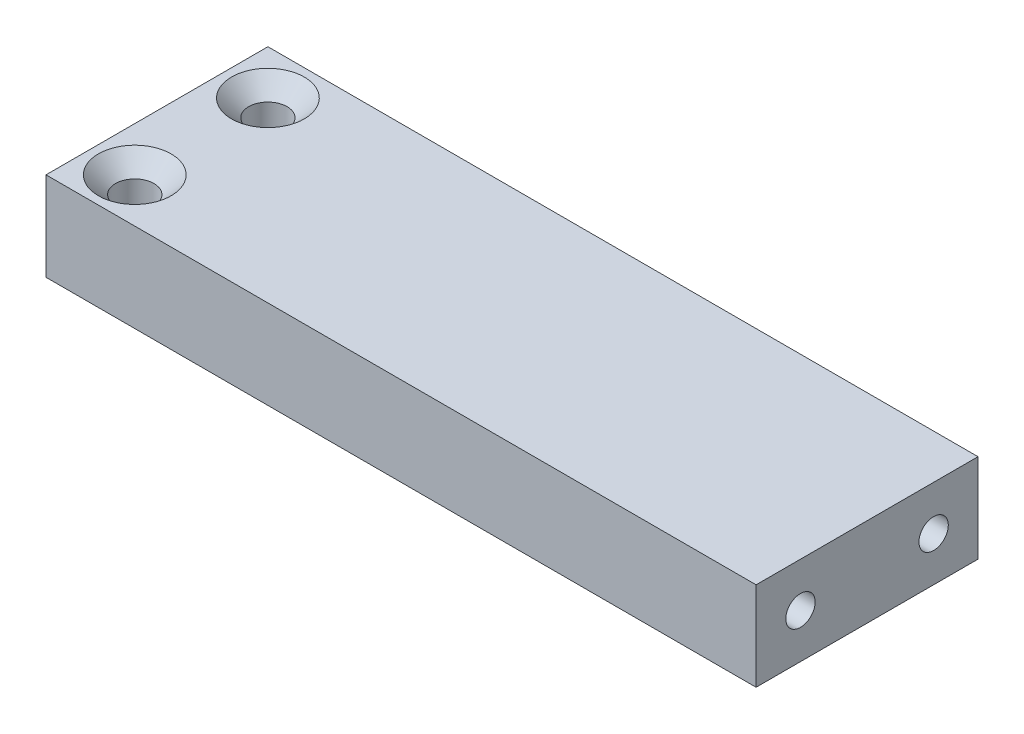
SolidWorks part; units mm, degrees
material "6061 Alloy"
ref_plane "Front" through (0, 0, 0) normal (0, 0, 1) x (1, 0, 0)
ref_plane "Top" through (0, 0, 0) normal (0, 1, 0) x (1, 0, 0)
ref_plane "Right" through (0, 0, 0) normal (1, 0, 0) x (0, 0, -1)
sketch "Sketch1" plane through (0, 0, 0) normal (0, 1, 0) x (1, 0, 0)
  line L1 (-50.8, -15.875) -> (50.8, -15.875)
  line L2 (-50.8, -15.875) -> (-50.8, 15.875)
  line L3 (-50.8, 15.875) -> (50.8, 15.875)
  line L4 (50.8, -15.875) -> (50.8, 15.875)
  line L5 (-50.8, -15.875) -> (50.8, 15.875) construction
  line L6 (-50.8, 15.875) -> (50.8, -15.875) construction
  point P0 (0, 0)
  dimension "D1" = 31.75
  dimension "D2" = 101.6
extrude "Boss-Extrude1" add sketch "Sketch1" along normal mid plane 12.7 contours L3 L4 L1 L2
sketch "Sketch2" plane through (50.8, 0, 0) normal (1, 0, 0) x (0, 0, -1)
  point P0 (-9.525, 0)
  point P1 (9.525, 0)
hole_wizard "M5x0.8 Tapped Hole1" positions "Sketch3" profile "Sketch5" tap size "M5x0.8" standard "ANSI Metric"
sketch "Sketch3" plane through (50.8, 0, 0) normal (1, 0, 0) x (0, 0, -1)
  point P0 (-9.525, 0)
  point P3 (9.525, 0)
sketch "Sketch5" plane through (50.8, 0, 9.525) normal (0, 1, 0) x (0, 0, -1)
  line L0 (0, 0) -> (0, 12.192)
  line L1 (0, 12.192) -> (2.1, 10.9302)
  line L2 (2.1, 10.9302) -> (2.1, 0)
  line L5 (2.1, 0) -> (0, 0)
  line L10 (0, 12.192) -> (-2.1, 10.9302) construction
  line L11 (0, -6.35) -> (0, 107.95) construction
  dimension "Tap Drill Dia." = 4.2
  dimension "Tap Drill Depth" = 12.192
  dimension "Drill Angle" = 118
cosmetic thread "Hole Thread2" parameters "D1"=9.906, "D2"=5
cosmetic thread "Hole Thread3" parameters "D1"=9.906, "D2"=5
sketch "Sketch6" plane through (0, 6.35, 0) normal (0, 1, 0) x (1, 0, 0)
  line L0 (-44.45, -9.525) -> (-44.45, 9.525) construction
  line L1 (-50.8, -15.875) -> (-50.8, 15.875) construction
  point P4 (-50.8, 0)
  point P5 (-44.45, 0)
  dimension "D1" = 19.05
  dimension "D2" = 6.35
hole_wizard "CSK for M5 Flat Head Machine Screw1" positions "Sketch7" profile "Sketch9" countersink size "M5" standard "ANSI Metric"
sketch "Sketch7" plane through (0, 6.35, 0) normal (0, 1, 0) x (1, 0, 0)
  point P0 (-44.45, -9.525)
  point P3 (-44.45, 9.525)
sketch "Sketch9" plane through (-44.45, 6.35, 9.525) normal (1, 0, 0) x (0, 0, 1)
  line L0 (0, 0) -> (0, 12.192)
  line L1 (0, 12.192) -> (2.75, 10.5396)
  line L2 (2.75, 10.5396) -> (2.75, 2.45)
  line L3 (2.75, 2.45) -> (5.2, 0)
  line L5 (5.2, 0) -> (0, 0)
  line L6 (-2.75, 2.45) -> (-5.2, 0) construction
  line L10 (0, 12.192) -> (-2.75, 10.5396) construction
  line L11 (0, -6.35) -> (0, 107.95) construction
  dimension "Hole Dia." = 5.5
  dimension "Hole Depth" = 12.192
  dimension "Near C'Sink Dia." = 10.4
  dimension "Near C'Sink Angle" = 90
  dimension "Drill Angle" = 118
